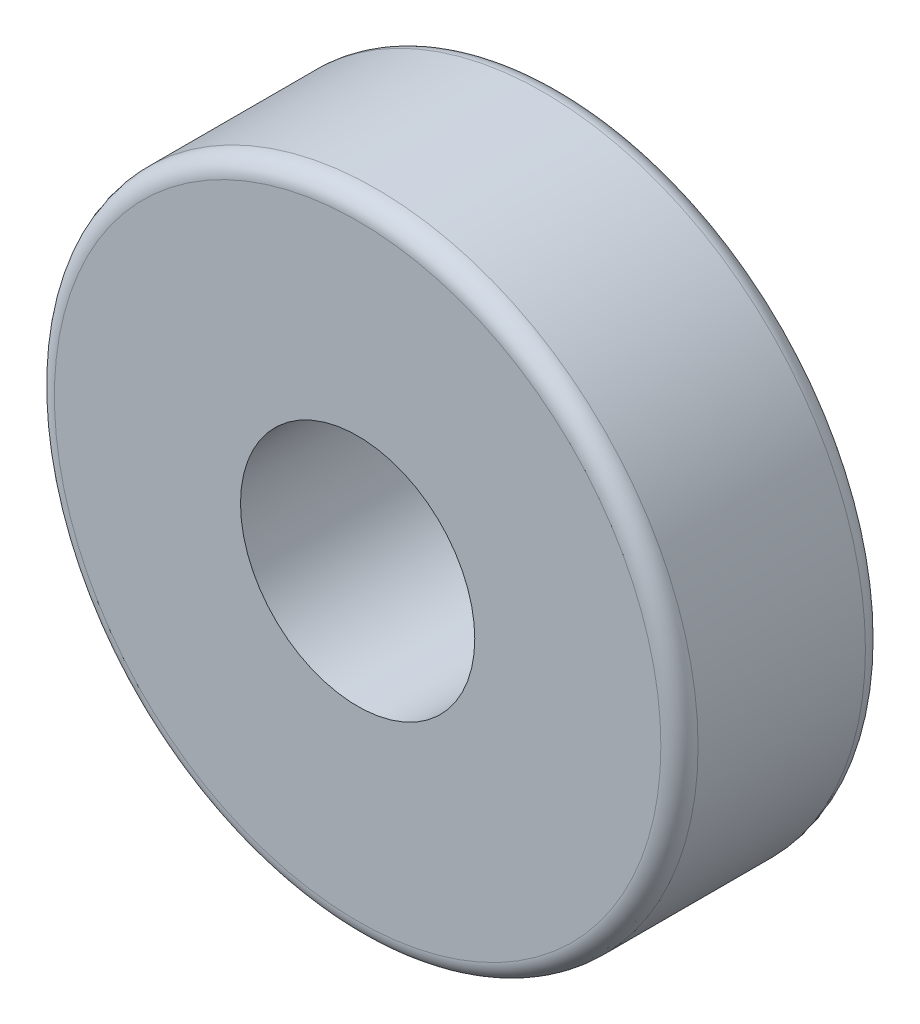
SolidWorks part; units mm, degrees
material "Plain Carbon Steel"
ref_plane "Front Plane" through (0, 0, 0) normal (0, 0, 1) x (1, 0, 0)
ref_plane "Top Plane" through (0, 0, 0) normal (0, 1, 0) x (1, 0, 0)
ref_plane "Right Plane" through (0, 0, 0) normal (1, 0, 0) x (0, 0, -1)
sketch "Sketch1" plane through (0, 0, 0) normal (0, 0, 1) x (1, 0, 0)
  circle A0 centre (0, 0) radius 10.9919
  circle A1 centre (0, 0) radius 4.0005
  dimension "D1" = 21.9837
  dimension "D2" = 8.001
extrude "Boss-Extrude1" add sketch "Sketch1" along normal blind 6.985
fillet "Fillet1" radius 0.635 2 edges at (10.9919, 0, 0) (10.9919, 0, 6.985)
